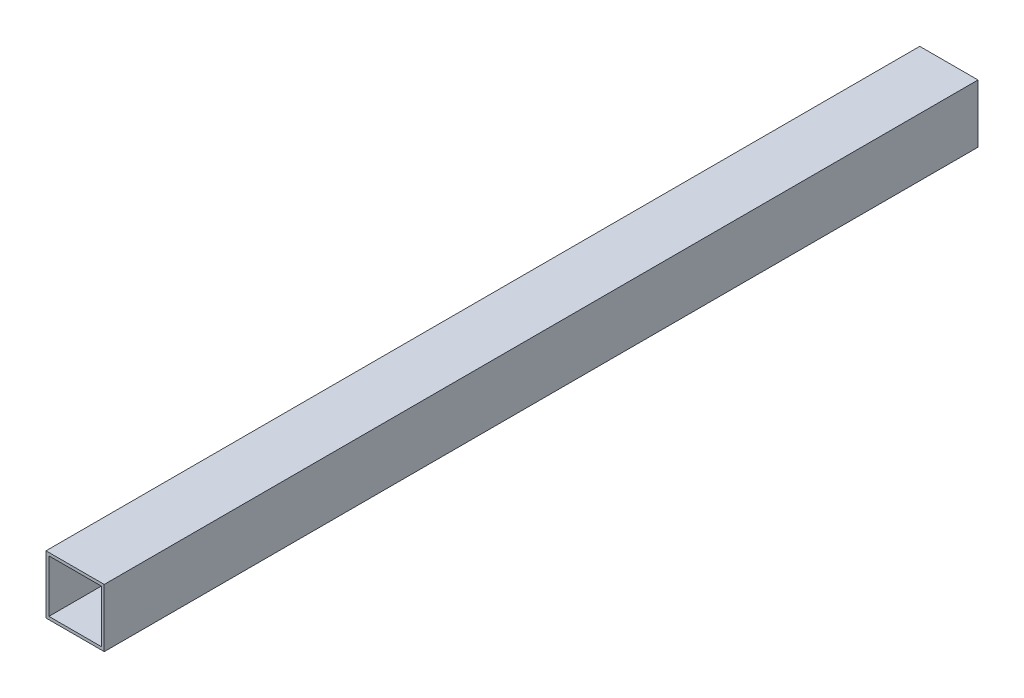
SolidWorks part; units mm, degrees
material "6061 Alloy"
ref_plane "Front Plane" through (0, 0, 0) normal (0, 0, 1) x (1, 0, 0)
ref_plane "Top Plane" through (0, 0, 0) normal (0, 1, 0) x (1, 0, 0)
ref_plane "Right Plane" through (0, 0, 0) normal (1, 0, 0) x (0, 0, -1)
sketch "Sketch3" plane through (0, 0, 0) normal (0, 0, 1) x (1, 0, 0)
  line L0 (-9, 9) -> (9, 9)
  line L1 (-10, -10) -> (10, -10)
  line L2 (-10, -10) -> (-10, 10)
  line L3 (-10, 10) -> (10, 10)
  line L4 (10, -10) -> (10, 10)
  line L5 (-10, -10) -> (10, 10) construction
  line L6 (-10, 10) -> (10, -10) construction
  line L7 (9, -9) -> (9, 9)
  line L8 (-9, -9) -> (9, -9)
  line L9 (-9, -9) -> (-9, 9)
  point P0 (0, 0)
  dimension "D1" = 20
  dimension "D2" = 20
  dimension "D3" = 1
extrude "Boss-Extrude1" add sketch "Sketch3" along normal blind 300
